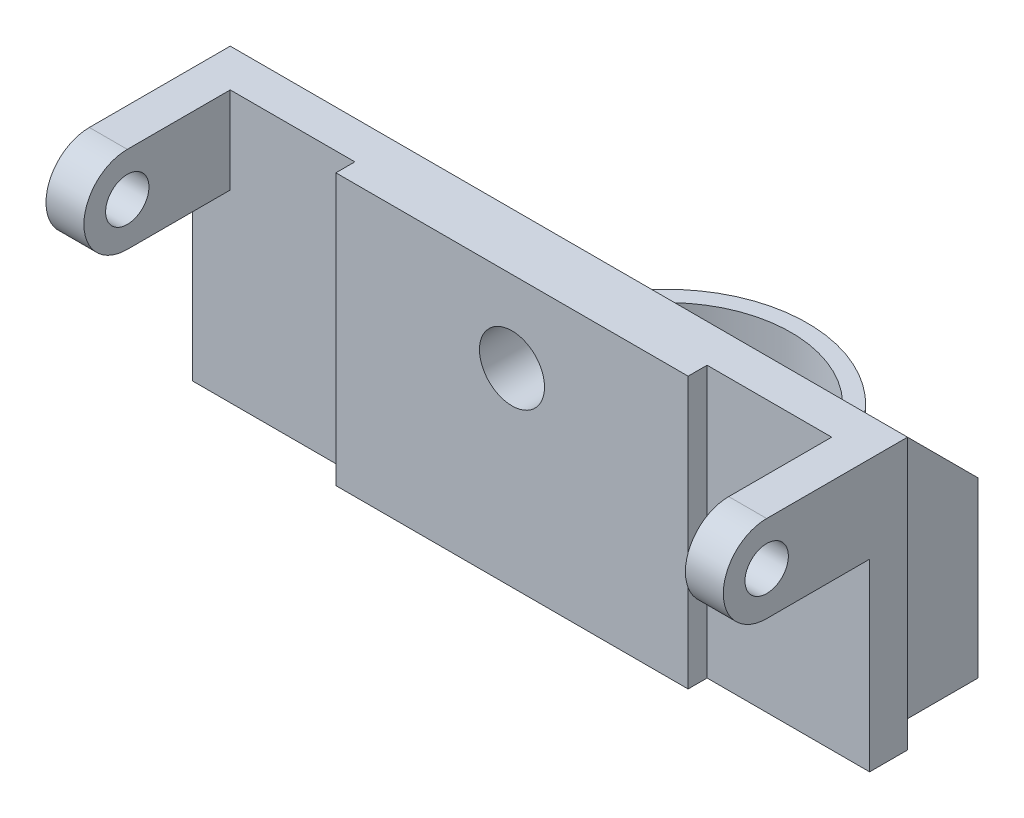
SolidWorks part; units mm, degrees
ref_plane "Front Plane" through (0, 0, 0) normal (0, 0, 1) x (1, 0, 0)
ref_plane "Top Plane" through (0, 0, 0) normal (0, 1, 0) x (1, 0, 0)
ref_plane "Right Plane" through (0, 0, 0) normal (1, 0, 0) x (0, 0, -1)
sketch "Sketch1" plane through (0, 0, 0) normal (0, 0, 1) x (1, 0, 0)
  line L1 (125, 50) -> (-125, 50)
  line L2 (125, 50) -> (125, -50)
  line L3 (125, -50) -> (-125, -50)
  line L4 (-125, 50) -> (-125, -50)
  line L5 (125, 50) -> (-125, -50) construction
  line L6 (125, -50) -> (-125, 50) construction
  point P0 (0, 0)
  dimension "D1" = 250
  dimension "D2" = 100
extrude "Boss-Extrude1" add sketch "Sketch1" along normal blind 14
sketch "Sketch2" plane through (0, 50, 0) normal (0, 1, 0) x (1, 0, 0)
  line L0 (0, 0) -> (0, -14) construction
  line L1 (125, -14) -> (-125, -14) construction
  line L2 (0, -14) -> (-65, -14)
  line L3 (-65, -14) -> (-65, -21)
  line L4 (-65, -21) -> (65, -21)
  line L5 (65, -21) -> (65, -14)
  line L6 (65, -14) -> (0, -14)
  dimension "D1" = 65
  dimension "D2" = 130
  dimension "D3" = 7
extrude "Boss-Extrude2" add sketch "Sketch2" against normal blind 100
sketch "Sketch7" plane through (-125, 0, 0) normal (-1, 0, 0) x (0, 0, 1)
  line L0 (14, 50) -> (14, 18)
  line L1 (14, 50) -> (14, -50) construction
  line L2 (14, 18) -> (52, 18)
  line L3 (52, 26) -> (52, 42)
  line L4 (52, 50) -> (14, 50)
  line L5 (14, 34) -> (52, 34) construction
  line L6 (52, 18) -> (52, 26) construction
  line L7 (52, 42) -> (52, 50) construction
  circle A0 centre (52, 34) radius 8
  arc A1 (52, 18) -> (52, 50) centre (52, 34) ccw
  arc A2 (52, 50) -> (36, 34) centre (52, 34) ccw construction
  arc A3 (36, 34) -> (52, 18) centre (52, 34) ccw construction
  dimension "D3" = 16
  dimension "D1" = 32
  dimension "D2" = 38
extrude "Boss-Extrude3" add sketch "Sketch7" against normal blind 14 contours L4 L0 L2 A1 | A0
mirror "Mirror1" about plane through (0, 0, 0) normal (1, 0, 0) of "Boss-Extrude1", "Boss-Extrude3"
sketch "Sketch8" plane through (0, 0, 0) normal (0, 0, -1) x (-1, 0, 0)
  line L0 (0, 50) -> (0, -50) construction
  line L1 (-125, 50) -> (125, 50) construction
  line L2 (125, -50) -> (-125, -50) construction
  circle A0 centre (0, 20) radius 12
  dimension "D1" = 24
  dimension "D2" = 30
extrude "Cut-Extrude1" cut sketch "Sketch8" against normal blind 25
sketch "Sketch10" plane through (0, -50, 0) normal (0, -1, 0) x (1, 0, 0)
  line L0 (115, 0) -> (115, -36)
  line L1 (-125, 0) -> (125, 0) construction
  line L2 (-52, -36) -> (-115, -36) construction
  line L3 (-115, -36) -> (-115, 0)
  line L4 (-115, 0) -> (115, 0)
  line L5 (125, 14) -> (125, 0) construction
  line L6 (0, -36) -> (0, 0) construction
  line L7 (115, -36) -> (23.513, -82.3803)
  line L8 (-115, -36) -> (-23.513, -82.3803)
  line L9 (115, -36) -> (52, -36) construction
  line L10 (52, -36) -> (0, -36) construction
  line L11 (0, -36) -> (-52, -36) construction
  arc A0 (-23.513, -82.3803) -> (23.513, -82.3803) centre (0, -36) ccw
  arc A1 (23.513, -82.3803) -> (52, -36) centre (0, -36) ccw construction
  arc A2 (52, -36) -> (37.5233, 0) centre (0, -36) ccw construction
  arc A3 (37.5233, 0) -> (-37.5233, 0) centre (0, -36) ccw construction
  arc A4 (-37.5233, 0) -> (-52, -36) centre (0, -36) ccw construction
  arc A5 (-52, -36) -> (-23.513, -82.3803) centre (0, -36) ccw construction
  dimension "D4" = 104
  dimension "D1" = 36
  dimension "D2" = 230
  dimension "D3" = 10
extrude "Boss-Extrude4" add sketch "Sketch10" against normal blind 15 separate body
sketch "Sketch12" plane through (115, 0, 0) normal (1, 0, 0) x (0, 0, -1)
  line L0 (0, -35) -> (0, 50)
  line L1 (36, -35) -> (36, 14)
  line L2 (36, 50) -> (0, 50) construction
  line L3 (36, -35) -> (0, -35)
  line L4 (0, 50) -> (36, 14)
  line L5 (36, 14) -> (36, 50) construction
  dimension "D1" = 36
extrude "Boss-Extrude5" add sketch "Sketch12" against normal blind 12
mirror "Mirror2" about plane through (0, 0, 0) normal (1, 0, 0) of "Boss-Extrude5"
sketch "Sketch13" plane through (0, -35, 0) normal (0, 1, 0) x (1, 0, 0)
  line L0 (0, 0) -> (0, 36) construction
  line L1 (-115, 36) -> (115, 36) construction
  circle A0 centre (0, 36) radius 7.5
  circle A1 centre (0, 36) radius 15
  arc A2 (24, 36) -> (-24, 36) centre (0, 36) ccw
  arc A3 (30, 36) -> (-30, 36) centre (0, 36) ccw
  arc A4 (-30, 36) -> (0, 6) centre (0, 36) ccw construction
  arc A5 (-24, 36) -> (0, 12) centre (0, 36) ccw construction
  arc A6 (0, 12) -> (24, 36) centre (0, 36) ccw construction
  arc A7 (0, 6) -> (30, 36) centre (0, 36) ccw construction
  arc A10 (46, 36) -> (-46, 36) centre (0, 36) ccw
  arc A11 (52, 36) -> (-52, 36) centre (0, 36) ccw
  arc A12 (-52, 36) -> (52, 36) centre (0, 36) ccw construction
  arc A13 (-46, 36) -> (46, 36) centre (0, 36) ccw construction
  arc A14 (-30, 36) -> (-46, 36) centre (-38, 36) cw
  arc A15 (-52, 36) -> (-24, 36) centre (-38, 36) ccw
  arc A16 (30, 36) -> (46, 36) centre (38, 36) ccw
  arc A17 (24, 36) -> (52, 36) centre (38, 36) ccw
  dimension "D2" = 15
  dimension "D3" = 30
  dimension "D4" = 48
  dimension "D5" = 60
  dimension "D6" = 92
  dimension "D7" = 104
  dimension "D1" = 36
extrude "Boss-Extrude6" add sketch "Sketch13" along normal blind 15
sketch "Sketch14" plane through (0, -35, 0) normal (0, 1, 0) x (1, 0, 0)
  line L0 (-115, 36) -> (115, 36) construction
  circle A0 centre (0, 36) radius 7.5
  arc A1 (30, 36) -> (-30, 36) centre (0, 36) ccw
  arc A2 (46, 36) -> (-46, 36) centre (0, 36) ccw
  arc A3 (-46, 36) -> (46, 36) centre (0, 36) ccw construction
  arc A4 (-30, 36) -> (30, 36) centre (0, 36) ccw construction
  arc A5 (-46, 36) -> (-30, 36) centre (-38, 36) ccw
  arc A6 (30, 36) -> (46, 36) centre (38, 36) ccw
  dimension "D1" = 15
  dimension "D2" = 60
  dimension "D3" = 92
extrude "Cut-Extrude2" cut sketch "Sketch14" against normal blind 15
